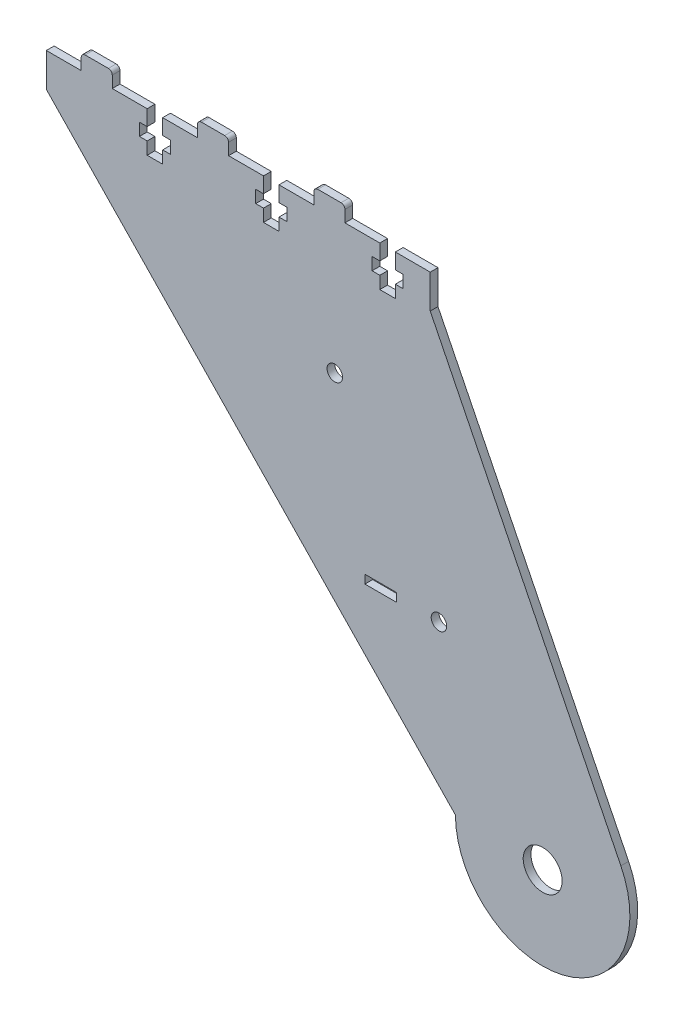
SolidWorks part; units mm, degrees
ref_plane "前视基准面" through (0, 0, 0) normal (0, 0, 1) x (1, 0, 0)
ref_plane "上视基准面" through (0, 0, 0) normal (0, 1, 0) x (1, 0, 0)
ref_plane "右视基准面" through (0, 0, 0) normal (1, 0, 0) x (0, 0, -1)
sketch "草图1" plane through (0, 0, 0) normal (0, 0, 1) x (1, 0, 0)
  line L2 (-36.15, 68.25) -> (-36.15, 58.15) construction
  line L15 (-38.15, 66.25) -> (-38.15, 62.25)
  line L16 (-38.15, 62.25) -> (-40.15, 62.25)
  line L17 (-40.15, 62.25) -> (-40.15, 59.05)
  line L18 (-40.15, 59.05) -> (-38.15, 59.05)
  line L19 (-38.15, 59.05) -> (-38.15, 55.85)
  line L20 (-38.15, 55.85) -> (-34.15, 55.85)
  line L21 (-38.15, 66.25) -> (-47.15, 66.25)
  line L22 (-51.15, 66.25) -> (-51.15, 70.25) construction
  line L23 (-47.15, 66.25) -> (-55.15, 66.25) construction
  line L24 (-47.15, 66.25) -> (-47.15, 70.25)
  line L25 (-47.15, 70.25) -> (-55.15, 70.25)
  line L26 (-55.15, 66.25) -> (-55.15, 70.25)
  line L27 (-25.15, 66.25) -> (-17.15, 66.25) construction
  line L28 (-21.15, 66.25) -> (-21.15, 70.25) construction
  line L29 (-17.15, 66.25) -> (-17.15, 70.25)
  line L30 (-25.15, 70.25) -> (-17.15, 70.25)
  line L31 (-25.15, 66.25) -> (-25.15, 70.25)
  line L32 (-34.15, 66.25) -> (-25.15, 66.25)
  line L33 (-34.15, 59.05) -> (-34.15, 55.85)
  line L34 (-32.15, 59.05) -> (-34.15, 59.05)
  line L35 (-32.15, 62.25) -> (-32.15, 59.05)
  line L36 (-34.15, 62.25) -> (-32.15, 62.25)
  line L37 (-34.15, 66.25) -> (-34.15, 62.25)
  line L38 (-94.15, 66.25) -> (-94.15, 57.55)
  line L39 (-94.15, 57.55) -> (11.35, -51.75)
  line L40 (-68.15, 66.25) -> (-68.15, 62.25)
  line L41 (-68.15, 62.25) -> (-70.15, 62.25)
  line L42 (-70.15, 62.25) -> (-70.15, 59.05)
  line L43 (-70.15, 59.05) -> (-68.15, 59.05)
  line L44 (-68.15, 59.05) -> (-68.15, 55.85)
  line L45 (-68.15, 66.25) -> (-77.15, 66.25)
  line L46 (-6.15, 68.25) -> (-6.15, 58.15) construction
  line L49 (-64.15, 55.85) -> (-68.15, 55.85)
  line L50 (-64.15, 59.05) -> (-64.15, 55.85)
  line L51 (-62.15, 59.05) -> (-64.15, 59.05)
  line L52 (-62.15, 62.25) -> (-62.15, 59.05)
  line L53 (-64.15, 62.25) -> (-62.15, 62.25)
  line L54 (-64.15, 66.25) -> (-64.15, 62.25)
  line L55 (-55.15, 66.25) -> (-64.15, 66.25)
  line L58 (-8.15, 66.25) -> (-17.15, 66.25)
  line L59 (-94.15, 66.25) -> (-85.15, 66.25)
  line L60 (-85.15, 66.25) -> (-85.15, 70.25)
  line L61 (-77.15, 70.25) -> (-85.15, 70.25)
  line L62 (-77.15, 66.25) -> (-77.15, 70.25)
  line L63 (4.85, 66.25) -> (4.85, 57.55)
  line L65 (7.0984, -10.75) -> (-7.9016, -10.75) construction
  line L66 (-8.15, 66.25) -> (-8.15, 62.25)
  line L67 (-8.15, 62.25) -> (-10.15, 62.25)
  line L68 (-10.15, 62.25) -> (-10.15, 59.05)
  line L69 (-10.15, 59.05) -> (-8.15, 59.05)
  line L70 (-8.15, 59.05) -> (-8.15, 55.85)
  line L74 (-4.15, 66.25) -> (4.85, 66.25)
  line L75 (-4.15, 55.85) -> (-8.15, 55.85)
  line L76 (-4.15, 59.05) -> (-4.15, 55.85)
  line L77 (-2.15, 59.05) -> (-4.15, 59.05)
  line L78 (-2.15, 62.25) -> (-2.15, 59.05)
  line L79 (-4.15, 62.25) -> (-2.15, 62.25)
  line L80 (-4.15, 66.25) -> (-4.15, 62.25)
  line L86 (4.85, 57.55) -> (54.0146, -41.7681)
  line L87 (-12.0016, -11.85) -> (-3.8016, -11.85)
  line L88 (-12.0016, -11.85) -> (-12.0016, -9.65)
  line L89 (-12.0016, -9.65) -> (-3.8016, -9.65)
  line L90 (-3.8016, -11.85) -> (-3.8016, -9.65)
  line L91 (-12.0016, -11.85) -> (-3.8016, -9.65) construction
  line L92 (-12.0016, -9.65) -> (-3.8016, -11.85) construction
  circle A0 centre (-36.15, 68.25) radius 2 construction
  circle A1 centre (-19.7627, 31.422) radius 2
  circle A2 centre (7.0984, -10.75) radius 2
  circle A3 centre (33.85, -51.75) radius 22.5 construction
  arc A6 (11.35, -51.75) -> (54.0146, -41.7681) centre (33.85, -51.75) ccw
  circle A7 centre (33.85, -52.75) radius 5.02
  point P39 (-36.15, 55.85)
  point P61 (-66.15, 55.85)
  point P91 (-6.15, 55.85)
  dimension "D17" = 10.04
  dimension "D20" = 4
  dimension "D12" = 4
  dimension "D5" = 4
  dimension "D6" = 2
  dimension "D7" = 3.2
  dimension "D8" = 3.2
  dimension "D9" = 15
  dimension "D10" = 8
  dimension "D11" = 4
  dimension "D13" = 8.2
  dimension "D14" = 2.2
  dimension "D15" = 10.1
  dimension "D16" = 15
extrude "凸台-拉伸1" add sketch "草图1" along normal blind 2
sketch "草图2" plane through (0, 66.25, 0) normal (0, 1, 0) x (1, 0, 0)
  line L0 (-8.15, -1) -> (-4.15, -1)
  line L1 (-8.15, -2) -> (-8.15, 0) construction
  line L2 (-4.15, -2) -> (-4.15, 0) construction
  circle A0 centre (-6.15, -1) radius 2
fillet "圆角1" radius 1 6 edges at (-17.15, 70.25, 1) (-25.15, 70.25, 1) (-47.15, 70.25, 1) (-55.15, 70.25, 1) (-77.15, 70.25, 1) (-85.15, 70.25, 1)
